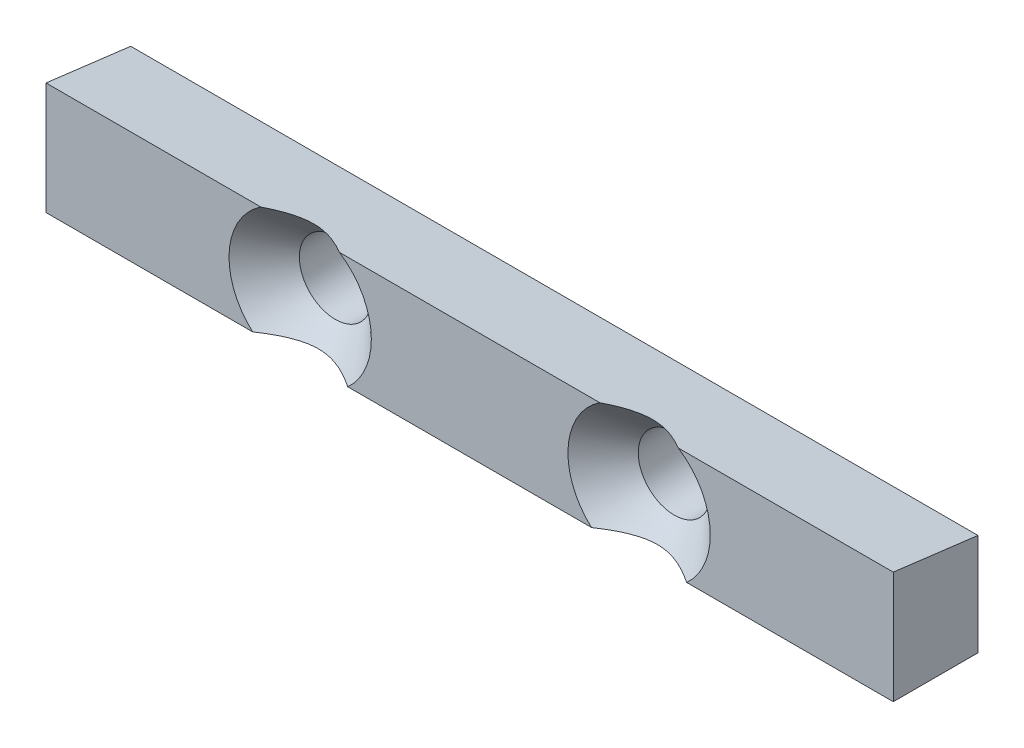
SolidWorks part; units mm, degrees
ref_plane "前视基准面" through (0, 0, 0) normal (0, 0, 1) x (1, 0, 0)
ref_plane "上视基准面" through (0, 0, 0) normal (0, 1, 0) x (1, 0, 0)
ref_plane "右视基准面" through (0, 0, 0) normal (1, 0, 0) x (0, 0, -1)
sketch "草图1" plane through (0, 0, 0) normal (0, 0, 1) x (1, 0, 0)
  line L1 (0, 0) -> (40, 0)
  line L2 (0, 0) -> (0, 5.3)
  line L3 (0, 5.3) -> (40, 5.3)
  line L4 (40, 0) -> (40, 5.3)
  dimension "D1" = 5.3
  dimension "D2" = 40
extrude "凸台-拉伸1" add sketch "草图1" along normal blind 4
sketch "草图2" plane through (40, 0, 0) normal (1, 0, 0) x (0, 0, -1)
  line L0 (-4, 5.3) -> (0, 5.3)
  line L1 (0, 5.3) -> (0, 4.8)
  line L2 (0, 0) -> (0, 5.3) construction
  line L3 (0, 4.8) -> (-4, 5.3)
  dimension "D1" = 0.5
extrude "切除-拉伸1" cut sketch "草图2" against normal through all
sketch "草图3" plane through (0, 0, 4) normal (0, 0, 1) x (1, 0, 0)
  line L0 (0, 2.5) -> (40, 2.5) construction
  line L3 (20, 5.3) -> (20, 0) construction
  line L4 (40, 5.3) -> (0, 5.3) construction
  line L5 (0, 0) -> (40, 0) construction
  circle A0 centre (12, 2.5) radius 1.5
  circle A1 centre (28, 2.5) radius 1.5
  dimension "D2" = 3
  dimension "D1" = 2.5
  dimension "D3" = 16
extrude "切除-拉伸2" cut sketch "草图3" against normal through all
hole_wizard "M3 六角凹锥坑螺钉的锥形沉头孔1" positions "3D草图1" profile "草图4" countersink size "M3" standard "ISO" end condition through all
sketch3d "3D草图1"
  line L0 (12, 2.5, 0) -> (12, 2.5, 4) construction
  line L1 (28, 2.5, 0) -> (28, 2.5, 4) construction
  point P0 (12, 2.5, 4)
  point P4 (28, 2.5, 4)
sketch "草图4" plane through (12, 2.5, 4) normal (1, 0, 0) x (0, -1, 0)
  line L0 (0, 0) -> (0, 4)
  line L1 (0, 4) -> (1.7, 4)
  line L2 (1.7, 4) -> (1.7, 1.66)
  line L3 (1.7, 1.66) -> (3.36, 0)
  line L5 (3.36, 0) -> (0, 0)
  line L6 (-1.7, 1.66) -> (-3.36, 0) construction
  line L11 (0, -6.35) -> (0, 107.95) construction
  dimension "通孔孔直径" = 3.4
  dimension "通孔孔深度" = 4
  dimension "近端锥形沉头孔直径" = 6.72
  dimension "近端锥形沉头孔角度" = 90
